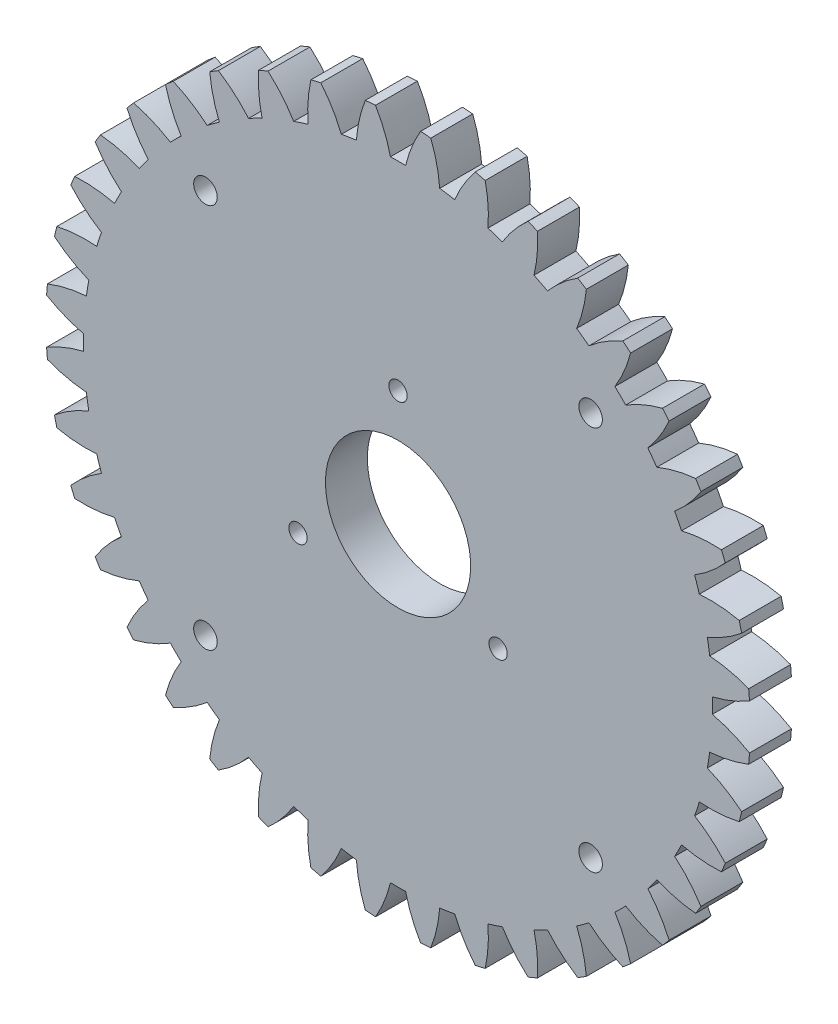
SolidWorks part; units mm, degrees
ref_plane "Front Plane" through (0, 0, 0) normal (0, 0, 1) x (1, 0, 0)
ref_plane "Top Plane" through (0, 0, 0) normal (0, 1, 0) x (1, 0, 0)
ref_plane "Right Plane" through (0, 0, 0) normal (1, 0, 0) x (0, 0, -1)
sketch "Sketch1" plane through (0, 0, 0) normal (0, 0, 1) x (1, 0, 0)
  line L0 (29.1682, 29.1682) -> (0, 0) construction
  line L1 (0, 0) -> (0, 41.25) construction
  circle A5 centre (0, 0) radius 41.25 construction
  circle A6 centre (29.1682, 29.1682) radius 1.7859
  circle A7 centre (29.1682, -29.1682) radius 1.7859
  circle A8 centre (-29.1682, -29.1682) radius 1.7859
  circle A9 centre (-29.1682, 29.1682) radius 1.7859
  point P14 (0, 0)
  point P26 (0, 0)
  circle B0 centre (0, 0) radius 19.05
  arc B1 (-53.2307, 3.4135) -> (-47.6099, 1.1483) centre (-42.9096, 20.9172) ccw
  arc B2 (-47.6099, 1.1483) -> (-47.6099, -1.1483) centre (0, 0) ccw
  arc B3 (-47.6099, -1.1483) -> (-53.2307, -3.4135) centre (-42.9096, -20.9172) ccw
  arc B4 (-53.2307, -3.4135) -> (-53.1093, -4.9556) centre (0, 0) ccw
  arc B5 (-53.1093, -4.9556) -> (-47.2034, -6.3137) centre (-45.6535, 13.9471) ccw
  arc B6 (-47.2034, -6.3137) -> (-46.8441, -8.582) centre (0, 0) ccw
  arc B7 (-46.8441, -8.582) -> (-52.0413, -11.6986) centre (-39.1091, -27.3722) ccw
  arc B8 (-52.0413, -11.6986) -> (-51.6802, -13.2027) centre (0, 0) ccw
  arc B9 (-51.6802, -13.2027) -> (-45.6345, -13.6202) centre (-47.2732, 6.6336) ccw
  arc B10 (-45.6345, -13.6202) -> (-44.9249, -15.8043) centre (0, 0) ccw
  arc B11 (-44.9249, -15.8043) -> (-49.5705, -19.6956) centre (-34.3457, -33.1532) ccw
  arc B12 (-49.5705, -19.6956) -> (-48.9786, -21.1248) centre (0, 0) ccw
  arc B13 (-48.9786, -21.1248) -> (-42.942, -20.5913) centre (-47.7289, -0.8432) ccw
  arc B14 (-42.942, -20.5913) -> (-41.8994, -22.6375) centre (0, 0) ccw
  arc B15 (-41.8994, -22.6375) -> (-45.8792, -27.2077) centre (-28.7365, -38.1179) ccw
  arc B16 (-45.8792, -27.2077) -> (-45.0709, -28.5266) centre (0, 0) ccw
  arc B17 (-45.0709, -28.5266) -> (-39.1921, -27.0554) centre (-47.0094, -8.2993) ccw
  arc B18 (-39.1921, -27.0554) -> (-37.8423, -28.9134) centre (0, 0) ccw
  arc B19 (-37.8423, -28.9134) -> (-41.0581, -34.0498) centre (-22.4198, -42.144) ccw
  arc B20 (-41.0581, -34.0498) -> (-40.0535, -35.226) centre (0, 0) ccw
  arc B21 (-40.0535, -35.226) -> (-34.4772, -32.8533) centre (-45.1323, -15.551) ccw
  arc B22 (-34.4772, -32.8533) -> (-32.8533, -34.4772) centre (0, 0) ccw
  arc B23 (-32.8533, -34.4772) -> (-35.226, -40.0535) centre (-15.551, -45.1323) ccw
  arc B24 (-35.226, -40.0535) -> (-34.0498, -41.0581) centre (0, 0) ccw
  arc B25 (-34.0498, -41.0581) -> (-28.9134, -37.8423) centre (-42.144, -22.4198) ccw
  arc B26 (-28.9134, -37.8423) -> (-27.0554, -39.1921) centre (0, 0) ccw
  arc B27 (-27.0554, -39.1921) -> (-28.5266, -45.0709) centre (-8.2993, -47.0094) ccw
  arc B28 (-28.5266, -45.0709) -> (-27.2077, -45.8792) centre (0, 0) ccw
  arc B29 (-27.2077, -45.8792) -> (-22.6375, -41.8994) centre (-38.1179, -28.7365) ccw
  arc B30 (-22.6375, -41.8994) -> (-20.5913, -42.942) centre (0, 0) ccw
  arc B31 (-20.5913, -42.942) -> (-21.1248, -48.9786) centre (-0.8432, -47.7289) ccw
  arc B32 (-21.1248, -48.9786) -> (-19.6956, -49.5705) centre (0, 0) ccw
  arc B33 (-19.6956, -49.5705) -> (-15.8043, -44.9249) centre (-33.1532, -34.3457) ccw
  arc B34 (-15.8043, -44.9249) -> (-13.6202, -45.6345) centre (0, 0) ccw
  arc B35 (-13.6202, -45.6345) -> (-13.2027, -51.6802) centre (6.6336, -47.2732) ccw
  arc B36 (-13.2027, -51.6802) -> (-11.6986, -52.0413) centre (0, 0) ccw
  arc B37 (-11.6986, -52.0413) -> (-8.582, -46.8441) centre (-27.3722, -39.1091) ccw
  arc B38 (-8.582, -46.8441) -> (-6.3137, -47.2034) centre (0, 0) ccw
  arc B39 (-6.3137, -47.2034) -> (-4.9556, -53.1093) centre (13.9471, -45.6535) ccw
  arc B40 (-4.9556, -53.1093) -> (-3.4135, -53.2307) centre (0, 0) ccw
  arc B41 (-3.4135, -53.2307) -> (-1.1483, -47.6099) centre (-20.9172, -42.9096) ccw
  arc B42 (-1.1483, -47.6099) -> (1.1483, -47.6099) centre (0, 0) ccw
  arc B43 (1.1483, -47.6099) -> (3.4135, -53.2307) centre (20.9172, -42.9096) ccw
  arc B44 (3.4135, -53.2307) -> (4.9556, -53.1093) centre (0, 0) ccw
  arc B45 (4.9556, -53.1093) -> (6.3137, -47.2034) centre (-13.9471, -45.6535) ccw
  arc B46 (6.3137, -47.2034) -> (8.582, -46.8441) centre (0, 0) ccw
  arc B47 (8.582, -46.8441) -> (11.6986, -52.0413) centre (27.3722, -39.1091) ccw
  arc B48 (11.6986, -52.0413) -> (13.2027, -51.6802) centre (0, 0) ccw
  arc B49 (13.2027, -51.6802) -> (13.6202, -45.6345) centre (-6.6336, -47.2732) ccw
  arc B50 (13.6202, -45.6345) -> (15.8043, -44.9249) centre (0, 0) ccw
  arc B51 (15.8043, -44.9249) -> (19.6956, -49.5705) centre (33.1532, -34.3457) ccw
  arc B52 (19.6956, -49.5705) -> (21.1248, -48.9786) centre (0, 0) ccw
  arc B53 (21.1248, -48.9786) -> (20.5913, -42.942) centre (0.8432, -47.7289) ccw
  arc B54 (20.5913, -42.942) -> (22.6375, -41.8994) centre (0, 0) ccw
  arc B55 (22.6375, -41.8994) -> (27.2077, -45.8792) centre (38.1179, -28.7365) ccw
  arc B56 (27.2077, -45.8792) -> (28.5266, -45.0709) centre (0, 0) ccw
  arc B57 (28.5266, -45.0709) -> (27.0554, -39.1921) centre (8.2993, -47.0094) ccw
  arc B58 (27.0554, -39.1921) -> (28.9134, -37.8423) centre (0, 0) ccw
  arc B59 (28.9134, -37.8423) -> (34.0498, -41.0581) centre (42.144, -22.4198) ccw
  arc B60 (34.0498, -41.0581) -> (35.226, -40.0535) centre (0, 0) ccw
  arc B61 (35.226, -40.0535) -> (32.8533, -34.4772) centre (15.551, -45.1323) ccw
  arc B62 (32.8533, -34.4772) -> (34.4772, -32.8533) centre (0, 0) ccw
  arc B63 (34.4772, -32.8533) -> (40.0535, -35.226) centre (45.1323, -15.551) ccw
  arc B64 (40.0535, -35.226) -> (41.0581, -34.0498) centre (0, 0) ccw
  arc B65 (41.0581, -34.0498) -> (37.8423, -28.9134) centre (22.4198, -42.144) ccw
  arc B66 (37.8423, -28.9134) -> (39.1921, -27.0554) centre (0, 0) ccw
  arc B67 (39.1921, -27.0554) -> (45.0709, -28.5266) centre (47.0094, -8.2993) ccw
  arc B68 (45.0709, -28.5266) -> (45.8792, -27.2077) centre (0, 0) ccw
  arc B69 (45.8792, -27.2077) -> (41.8994, -22.6375) centre (28.7365, -38.1179) ccw
  arc B70 (41.8994, -22.6375) -> (42.942, -20.5913) centre (0, 0) ccw
  arc B71 (42.942, -20.5913) -> (48.9786, -21.1248) centre (47.7289, -0.8432) ccw
  arc B72 (48.9786, -21.1248) -> (49.5705, -19.6956) centre (0, 0) ccw
  arc B73 (49.5705, -19.6956) -> (44.9249, -15.8043) centre (34.3457, -33.1532) ccw
  arc B74 (44.9249, -15.8043) -> (45.6345, -13.6202) centre (0, 0) ccw
  arc B75 (45.6345, -13.6202) -> (51.6802, -13.2027) centre (47.2732, 6.6336) ccw
  arc B76 (51.6802, -13.2027) -> (52.0413, -11.6986) centre (0, 0) ccw
  arc B77 (52.0413, -11.6986) -> (46.8441, -8.582) centre (39.1091, -27.3722) ccw
  arc B78 (46.8441, -8.582) -> (47.2034, -6.3137) centre (0, 0) ccw
  arc B79 (47.2034, -6.3137) -> (53.1093, -4.9556) centre (45.6535, 13.9471) ccw
  arc B80 (53.1093, -4.9556) -> (53.2307, -3.4135) centre (0, 0) ccw
  arc B81 (53.2307, -3.4135) -> (47.6099, -1.1483) centre (42.9096, -20.9172) ccw
  arc B82 (47.6099, -1.1483) -> (47.6099, 1.1483) centre (0, 0) ccw
  arc B83 (47.6099, 1.1483) -> (53.2307, 3.4135) centre (42.9096, 20.9172) ccw
  arc B84 (53.2307, 3.4135) -> (53.1093, 4.9556) centre (0, 0) ccw
  arc B85 (53.1093, 4.9556) -> (47.2034, 6.3137) centre (45.6535, -13.9471) ccw
  arc B86 (47.2034, 6.3137) -> (46.8441, 8.582) centre (0, 0) ccw
  arc B87 (46.8441, 8.582) -> (52.0413, 11.6986) centre (39.1091, 27.3722) ccw
  arc B88 (52.0413, 11.6986) -> (51.6802, 13.2027) centre (0, 0) ccw
  arc B89 (51.6802, 13.2027) -> (45.6345, 13.6202) centre (47.2732, -6.6336) ccw
  arc B90 (45.6345, 13.6202) -> (44.9249, 15.8043) centre (0, 0) ccw
  arc B91 (44.9249, 15.8043) -> (49.5705, 19.6956) centre (34.3457, 33.1532) ccw
  arc B92 (49.5705, 19.6956) -> (48.9786, 21.1248) centre (0, 0) ccw
  arc B93 (48.9786, 21.1248) -> (42.942, 20.5913) centre (47.7289, 0.8432) ccw
  arc B94 (42.942, 20.5913) -> (41.8994, 22.6375) centre (0, 0) ccw
  arc B95 (41.8994, 22.6375) -> (45.8792, 27.2077) centre (28.7365, 38.1179) ccw
  arc B96 (45.8792, 27.2077) -> (45.0709, 28.5266) centre (0, 0) ccw
  arc B97 (45.0709, 28.5266) -> (39.1921, 27.0554) centre (47.0094, 8.2993) ccw
  arc B98 (39.1921, 27.0554) -> (37.8423, 28.9134) centre (0, 0) ccw
  arc B99 (37.8423, 28.9134) -> (41.0581, 34.0498) centre (22.4198, 42.144) ccw
  arc B100 (41.0581, 34.0498) -> (40.0535, 35.226) centre (0, 0) ccw
  arc B101 (40.0535, 35.226) -> (34.4772, 32.8533) centre (45.1323, 15.551) ccw
  arc B102 (34.4772, 32.8533) -> (32.8533, 34.4772) centre (0, 0) ccw
  arc B103 (32.8533, 34.4772) -> (35.226, 40.0535) centre (15.551, 45.1323) ccw
  arc B104 (35.226, 40.0535) -> (34.0498, 41.0581) centre (0, 0) ccw
  arc B105 (34.0498, 41.0581) -> (28.9134, 37.8423) centre (42.144, 22.4198) ccw
  arc B106 (28.9134, 37.8423) -> (27.0554, 39.1921) centre (0, 0) ccw
  arc B107 (27.0554, 39.1921) -> (28.5266, 45.0709) centre (8.2993, 47.0094) ccw
  arc B108 (28.5266, 45.0709) -> (27.2077, 45.8792) centre (0, 0) ccw
  arc B109 (27.2077, 45.8792) -> (22.6375, 41.8994) centre (38.1179, 28.7365) ccw
  arc B110 (22.6375, 41.8994) -> (20.5913, 42.942) centre (0, 0) ccw
  arc B111 (20.5913, 42.942) -> (21.1248, 48.9786) centre (0.8432, 47.7289) ccw
  arc B112 (21.1248, 48.9786) -> (19.6956, 49.5705) centre (0, 0) ccw
  arc B113 (19.6956, 49.5705) -> (15.8043, 44.9249) centre (33.1532, 34.3457) ccw
  arc B114 (15.8043, 44.9249) -> (13.6202, 45.6345) centre (0, 0) ccw
  arc B115 (13.6202, 45.6345) -> (13.2027, 51.6802) centre (-6.6336, 47.2732) ccw
  arc B116 (13.2027, 51.6802) -> (11.6986, 52.0413) centre (0, 0) ccw
  arc B117 (11.6986, 52.0413) -> (8.582, 46.8441) centre (27.3722, 39.1091) ccw
  arc B118 (8.582, 46.8441) -> (6.3137, 47.2034) centre (0, 0) ccw
  arc B119 (6.3137, 47.2034) -> (4.9556, 53.1093) centre (-13.9471, 45.6535) ccw
  arc B120 (4.9556, 53.1093) -> (3.4135, 53.2307) centre (0, 0) ccw
  arc B121 (3.4135, 53.2307) -> (1.1483, 47.6099) centre (20.9172, 42.9096) ccw
  arc B122 (1.1483, 47.6099) -> (-1.1483, 47.6099) centre (0, 0) ccw
  arc B123 (-1.1483, 47.6099) -> (-3.4135, 53.2307) centre (-20.9172, 42.9096) ccw
  arc B124 (-3.4135, 53.2307) -> (-4.9556, 53.1093) centre (0, 0) ccw
  arc B125 (-4.9556, 53.1093) -> (-6.3137, 47.2034) centre (13.9471, 45.6535) ccw
  arc B126 (-6.3137, 47.2034) -> (-8.582, 46.8441) centre (0, 0) ccw
  arc B127 (-8.582, 46.8441) -> (-11.6986, 52.0413) centre (-27.3722, 39.1091) ccw
  arc B128 (-11.6986, 52.0413) -> (-13.2027, 51.6802) centre (0, 0) ccw
  arc B129 (-13.2027, 51.6802) -> (-13.6202, 45.6345) centre (6.6336, 47.2732) ccw
  arc B130 (-13.6202, 45.6345) -> (-15.8043, 44.9249) centre (0, 0) ccw
  arc B131 (-15.8043, 44.9249) -> (-19.6956, 49.5705) centre (-33.1532, 34.3457) ccw
  arc B132 (-19.6956, 49.5705) -> (-21.1248, 48.9786) centre (0, 0) ccw
  arc B133 (-21.1248, 48.9786) -> (-20.5913, 42.942) centre (-0.8432, 47.7289) ccw
  arc B134 (-20.5913, 42.942) -> (-22.6375, 41.8994) centre (0, 0) ccw
  arc B135 (-22.6375, 41.8994) -> (-27.2077, 45.8792) centre (-38.1179, 28.7365) ccw
  arc B136 (-27.2077, 45.8792) -> (-28.5266, 45.0709) centre (0, 0) ccw
  arc B137 (-28.5266, 45.0709) -> (-27.0554, 39.1921) centre (-8.2993, 47.0094) ccw
  arc B138 (-27.0554, 39.1921) -> (-28.9134, 37.8423) centre (0, 0) ccw
  arc B139 (-28.9134, 37.8423) -> (-34.0498, 41.0581) centre (-42.144, 22.4198) ccw
  arc B140 (-34.0498, 41.0581) -> (-35.226, 40.0535) centre (0, 0) ccw
  arc B141 (-35.226, 40.0535) -> (-32.8533, 34.4772) centre (-15.551, 45.1323) ccw
  arc B142 (-32.8533, 34.4772) -> (-34.4772, 32.8533) centre (0, 0) ccw
  arc B143 (-34.4772, 32.8533) -> (-40.0535, 35.226) centre (-45.1323, 15.551) ccw
  arc B144 (-40.0535, 35.226) -> (-41.0581, 34.0498) centre (0, 0) ccw
  arc B145 (-41.0581, 34.0498) -> (-37.8423, 28.9134) centre (-22.4198, 42.144) ccw
  arc B146 (-37.8423, 28.9134) -> (-39.1921, 27.0554) centre (0, 0) ccw
  arc B147 (-39.1921, 27.0554) -> (-45.0709, 28.5266) centre (-47.0094, 8.2993) ccw
  arc B148 (-45.0709, 28.5266) -> (-45.8792, 27.2077) centre (0, 0) ccw
  arc B149 (-45.8792, 27.2077) -> (-41.8994, 22.6375) centre (-28.7365, 38.1179) ccw
  arc B150 (-41.8994, 22.6375) -> (-42.942, 20.5913) centre (0, 0) ccw
  arc B151 (-42.942, 20.5913) -> (-48.9786, 21.1248) centre (-47.7289, 0.8432) ccw
  arc B152 (-48.9786, 21.1248) -> (-49.5705, 19.6956) centre (0, 0) ccw
  arc B153 (-49.5705, 19.6956) -> (-44.9249, 15.8043) centre (-34.3457, 33.1532) ccw
  arc B154 (-44.9249, 15.8043) -> (-45.6345, 13.6202) centre (0, 0) ccw
  arc B155 (-45.6345, 13.6202) -> (-51.6802, 13.2027) centre (-47.2732, -6.6336) ccw
  arc B156 (-51.6802, 13.2027) -> (-52.0413, 11.6986) centre (0, 0) ccw
  arc B157 (-52.0413, 11.6986) -> (-46.8441, 8.582) centre (-39.1091, 27.3722) ccw
  arc B158 (-46.8441, 8.582) -> (-47.2034, 6.3137) centre (0, 0) ccw
  arc B159 (-47.2034, 6.3137) -> (-53.1093, 4.9556) centre (-45.6535, -13.9471) ccw
  arc B160 (-53.1093, 4.9556) -> (-53.2307, 3.4135) centre (0, 0) ccw
  dimension "D4" = 82.5
  dimension "D5" = 3.5719
  dimension "D6" = 45
  dimension "D7" = 4
sketch_block_instance "Drive_Spur_Encoder_2-1"
sketch_block "Drive_Spur_Encoder_2"
extrude "Boss-Extrude1" add sketch "Sketch1" along normal blind 6.35
sketch "Sketch2" plane through (0, 0, 6.35) normal (0, 0, 1) x (1, 0, 0)
  circle A0 centre (0, 0) radius 19.05
extrude "Boss-Extrude2" add sketch "Sketch2" against normal up to surface (6.35 mm away) up to face at (0, 0, 0)
sketch "Sketch3" plane through (0, 0, 0) normal (0, 0, -1) x (-1, 0, 0)
  circle A0 centre (0, 0) radius 11
  circle A1 centre (0, 0) radius 17.5 construction
  circle A2 centre (0, 17.5) radius 1.3891
  circle A3 centre (15.1554, -8.75) radius 1.3891
  circle A4 centre (-15.1554, -8.75) radius 1.3891
  point P12 (0, 0)
  dimension "D1" = 22
  dimension "D2" = 35
  dimension "D3" = 2.7781
  dimension "D4" = 3
extrude "Cut-Extrude1" cut sketch "Sketch3" against normal through all
